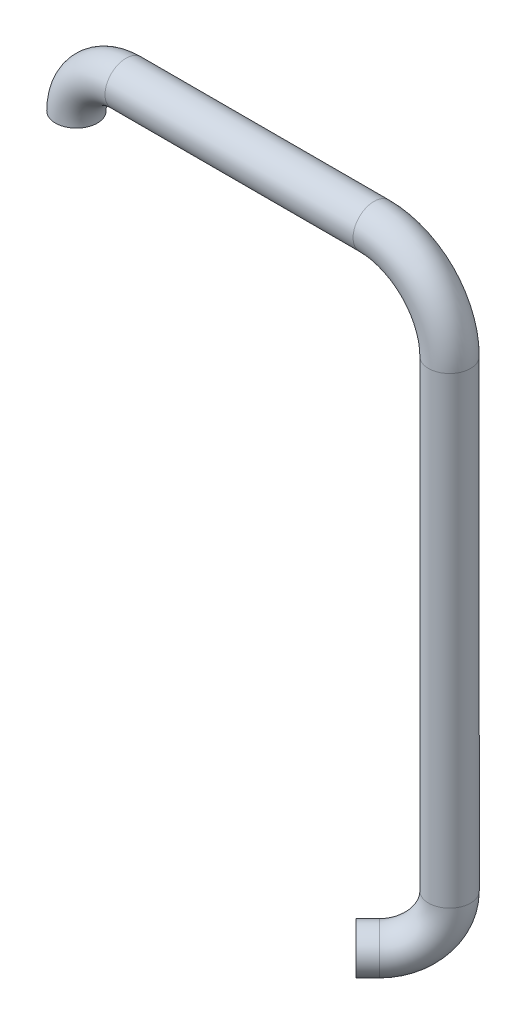
SolidWorks part; units mm, degrees
ref_plane "Front Plane" through (0, 0, 0) normal (0, 0, 1) x (1, 0, 0)
ref_plane "Top Plane" through (0, 0, 0) normal (0, 1, 0) x (1, 0, 0)
ref_plane "Right Plane" through (0, 0, 0) normal (1, 0, 0) x (0, 0, -1)
sketch3d "3DSketch1"
  line L0 (7.8327, 15.6654, 4.1975) -> (157.8327, 15.6654, 4.1975)
  line L1 (203.498, -30, 4.1975) -> (203.498, -310, 4.1975)
  line L5 (182.2848, -340, 25.4107) -> (175.2138, -340, 32.4818)
  arc A0 (203.498, -310, 4.1975) -> (182.2848, -340, 25.4107) centre (182.2848, -310, 25.4107) ccw
  arc A1 (157.8327, 15.6654, 4.1975) -> (203.498, -30, 4.1975) centre (157.8327, -30, 4.1975) ccw
  arc A2 (7.8327, 15.6654, 4.1975) -> (-22.1673, -14.3346, 4.1975) centre (7.8327, -14.3346, 4.1975) ccw
  point P5 (203.498, -340, 4.1975)
  point P8 (161.0716, -310, 4.1975)
  point P11 (203.498, 15.6654, 4.1975)
  point P12 (157.8327, -30, -41.4678)
  point P16 (0, 0, 0)
  point P17 (7.8327, -14.3346, 34.1975)
  dimension "D3" = 150
  dimension "D2" = 40
  dimension "D1" = 30
sweep "Sweep3" add path "3DSketch1" circular profile diameter 25.4 parameters "D3"=25.4
shell "Shell2" thickness 3
